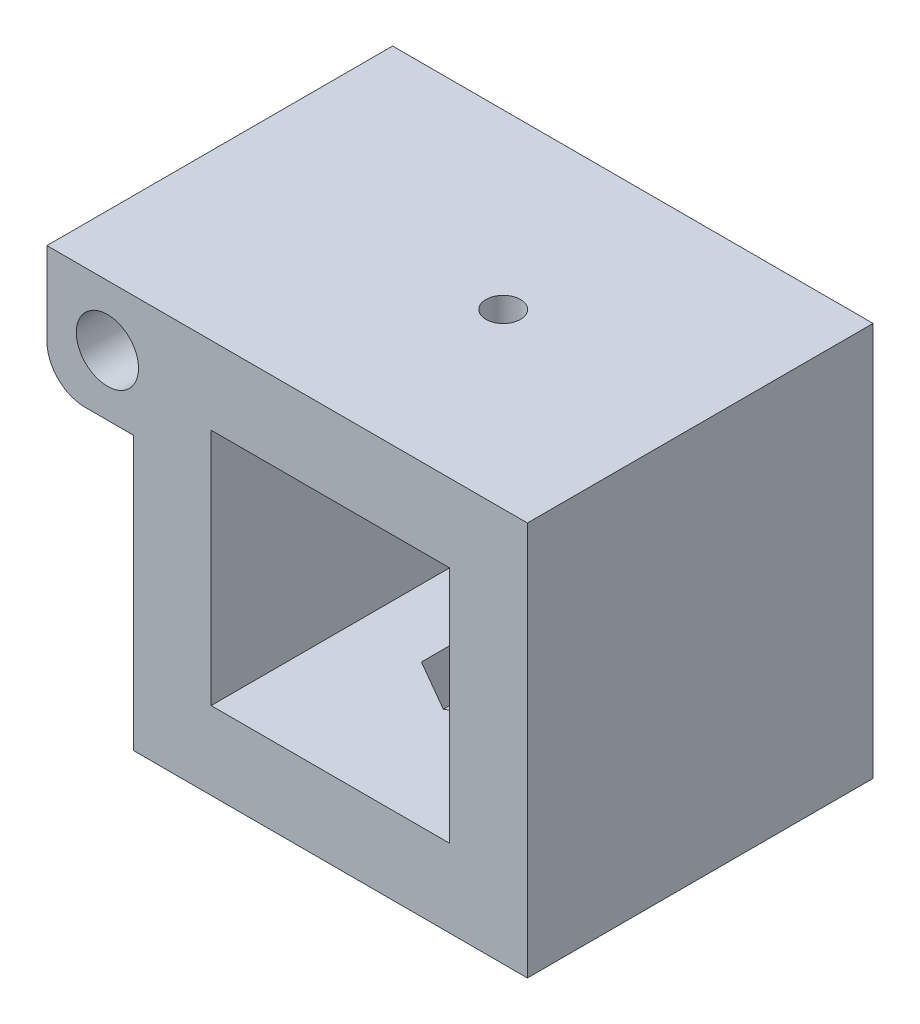
SolidWorks part; units mm, degrees
ref_plane "Alzado" through (0, 0, 0) normal (0, 0, 1) x (1, 0, 0)
ref_plane "Planta" through (0, 0, 0) normal (0, 1, 0) x (1, 0, 0)
ref_plane "Vista lateral" through (0, 0, 0) normal (1, 0, 0) x (0, 0, -1)
sketch "Croquis1" plane through (0, 0, 0) normal (0, 0, 1) x (1, 0, 0)
  line L0 (-11.4, -11.4) -> (-11.4, 11.4)
  line L1 (-6.9, -6.9) -> (6.9, -6.9)
  line L2 (-6.9, -6.9) -> (-6.9, 6.9)
  line L3 (-6.9, 6.9) -> (6.9, 6.9)
  line L4 (6.9, -6.9) -> (6.9, 6.9)
  line L5 (-6.9, -6.9) -> (6.9, 6.9) construction
  line L6 (-6.9, 6.9) -> (6.9, -6.9) construction
  line L7 (-11.4, 11.4) -> (11.4, 11.4)
  line L8 (11.4, -11.4) -> (11.4, 11.4)
  line L9 (-11.4, -11.4) -> (11.4, -11.4)
  point P0 (0, 0)
  dimension "D1" = 13.8
  dimension "D2" = 13.8
  dimension "D3" = 4.5
extrude "Saliente-Extruir1" add sketch "Croquis1" along normal mid plane 20
sketch "Croquis2" plane through (0, -6.9, 0) normal (0, 1, 0) x (1, 0, 0)
  line L1 (3, -1.7321) -> (3, 1.7321)
  line L2 (3, 1.7321) -> (0, 3.4641)
  line L3 (0, 3.4641) -> (-3, 1.7321)
  line L4 (-3, 1.7321) -> (-3, -1.7321)
  line L5 (-3, -1.7321) -> (0, -3.4641)
  line L6 (0, -3.4641) -> (3, -1.7321)
  circle A0 centre (0, 0) radius 3 construction
  dimension "D1" = 6
extrude "Cortar-Extruir1" cut sketch "Croquis2" against normal blind 3
sketch "Croquis3" plane through (0, -9.9, 0) normal (0, 1, 0) x (1, 0, 0)
  circle A0 centre (0, 0) radius 1.75
  dimension "D1" = 3.5
extrude "Cortar-Extruir2" cut sketch "Croquis3" against normal blind 3
sketch "Croquis4" plane through (0, 0, 10) normal (0, 0, -1) x (-1, 0, 0)
  line L0 (12.9, 11.4) -> (12.9, 4.4) construction
  line L1 (11.4, 11.4) -> (16.4, 11.4)
  line L2 (11.4, 11.4) -> (11.4, 4.4)
  line L3 (11.4, 4.4) -> (16.4, 4.4)
  line L4 (-11.4, -11.4) -> (11.4, -11.4)
  line L5 (11.4, -11.4) -> (11.4, 11.4)
  line L6 (11.4, 11.4) -> (-11.4, 11.4)
  line L7 (-11.4, 11.4) -> (-11.4, -11.4)
  line L8 (-11.4, -11.4) -> (11.4, -11.4)
  line L9 (11.4, -11.4) -> (11.4, 11.4)
  line L10 (11.4, 11.4) -> (-11.4, 11.4)
  line L11 (-11.4, 11.4) -> (-11.4, -11.4)
  line L12 (16.4, 11.4) -> (16.4, 4.4)
  circle A0 centre (12.9, 7.9) radius 1.6
  line M26 (11.4, 11.4) -> (11.4, -11.4)
  dimension "D2" = 3.2
  dimension "D3" = 5
  dimension "D4" = 1.5
  dimension "D5" = 7
  dimension "D1" = 0
extrude "Saliente-Extruir3" add sketch "Croquis4" along normal blind 20 contours L0 L1 L12 L3 A0 | A0 L0 L3 M26 | L1 L0 A0 M26
hole_wizard "Refrentado para tornillo con cabeza plana de M32" positions "Croquis3D2" profile "Croquis13" counterbore size "M3" standard "ISO" end condition through all
sketch3d "Croquis3D2"
  line L0 (-12.9, 7.9, -10) -> (-12.9, 7.9, 10) construction
  point P0 (-12.9, 7.9, -10)
sketch "Croquis13" plane through (-12.9, 7.9, -10) normal (1, 0, 0) x (0, 1, 0)
  line L0 (0, 0) -> (0, 20)
  line L1 (0, 20) -> (1.8, 20)
  line L3 (1.8, 20) -> (1.8, 2)
  line L4 (1.8, 2) -> (3.25, 2)
  line L5 (3.25, 2) -> (3.25, 0)
  line L7 (3.25, 0) -> (0, 0)
  line L11 (0, -6.35) -> (0, 107.95) construction
  dimension "Diámetro de taladro hasta el siguiente" = 3.6
  dimension "Profundidad de taladro hasta el siguiente" = 20
  dimension "Diámetro de refrentado" = 6.5
  dimension "Profundidad de refrentado" = 2
sketch "Croquis8" plane through (0, 0, -10) normal (0, 0, -1) x (-1, 0, 0)
  circle A2 centre (12.9, 7.9) radius 3.25
  circle A3 centre (12.9, 7.9) radius 3.25 construction
fillet "Redondeo1" radius 2.2 1 edges at (-16.4, 4.4, 0)
sketch "Croquis12" plane through (0, 11.4, 0) normal (0, 1, 0) x (1, 0, 0)
  circle A0 centre (0, 0) radius 1
  dimension "D1" = 2
extrude "Cortar-Extruir5" cut sketch "Croquis12" against normal blind 10
